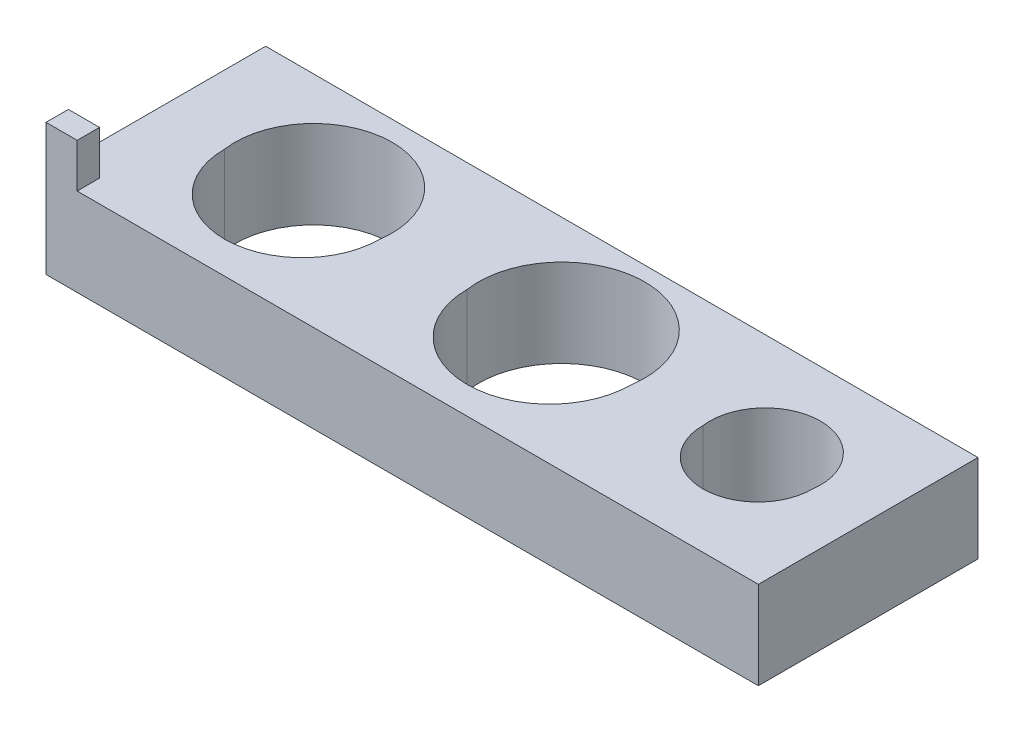
SolidWorks part; units mm, degrees
ref_plane "Front" through (0, 0, 0) normal (0, 0, 1) x (1, 0, 0)
ref_plane "Top" through (0, 0, 0) normal (0, 1, 0) x (1, 0, 0)
ref_plane "Right" through (0, 0, 0) normal (1, 0, 0) x (0, 0, -1)
sketch "Sketch1" plane through (0, 0, 0) normal (0, 1, 0) x (1, 0, 0)
  line L0 (0, 6.35) -> (38.1, 6.35)
  line L1 (0, 0) -> (38.1, 0)
  line L2 (0, 0) -> (0, 12.7)
  line L3 (0, 12.7) -> (38.1, 12.7)
  line L4 (38.1, 0) -> (38.1, 12.7)
  line L6 (0, 12.7) -> (-3.0858, 12.7)
  line L7 (0, 12.7) -> (0, 0)
  line L8 (0, 0) -> (-3.0858, 0)
  line L9 (-3.0858, 12.7) -> (-3.0858, 0)
  circle A0 centre (5.3798, 6.35) radius 4.5
  circle A2 centre (31.7225, 6.35) radius 3.175
  circle A3 centre (19.6779, 6.35) radius 4.7625
  arc A4 (0.8798, 6.35) -> (9.8798, 6.35) centre (5.3798, 7.0029) cw
  arc A5 (14.9154, 6.35) -> (24.4404, 6.35) centre (19.6779, 7.0475) cw
  arc A6 (28.5475, 6.35) -> (34.8975, 6.35) centre (31.7225, 6.7666) cw
  dimension "D1" = 12.7
  dimension "D2" = 38.1
extrude "Boss-Extrude1" add sketch "Sketch1" along normal blind 5.08 contours A3 L0 A0 L2 L1 L4 A2 | A3 L0 A2 L4 L3 L2 A0 | L7 L6 L9 L8
sketch "Sketch3" plane through (0, 5.08, 0) normal (0, 1, 0) x (1, 0, 0)
  line L1 (-3.0858, 0) -> (-1.2839, 0)
  line L2 (-3.0858, 0) -> (-3.0858, 1.2941)
  line L3 (-3.0858, 1.2941) -> (-1.2839, 1.2941)
  line L4 (-1.2839, 0) -> (-1.2839, 1.2941)
extrude "Boss-Extrude2" add sketch "Sketch3" along normal blind 2.54
